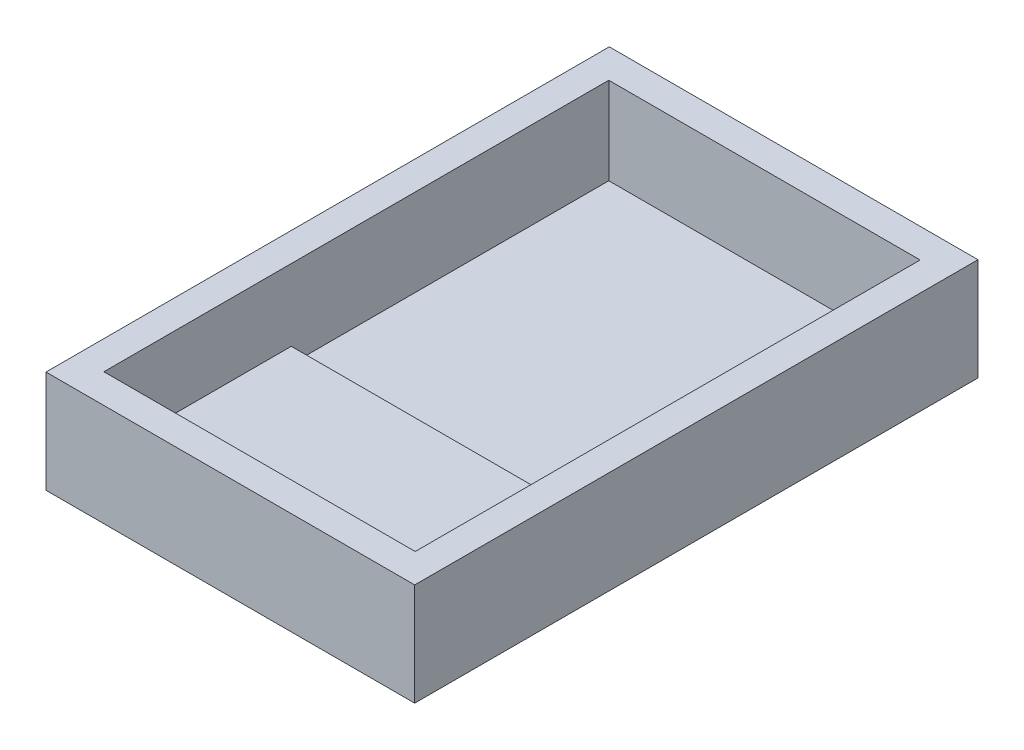
SolidWorks part; units mm, degrees
ref_plane "Front Plane" through (0, 0, 0) normal (0, 0, 1) x (1, 0, 0)
ref_plane "Top Plane" through (0, 0, 0) normal (0, 1, 0) x (1, 0, 0)
ref_plane "Right Plane" through (0, 0, 0) normal (1, 0, 0) x (0, 0, -1)
sketch "Sketch1" plane through (0, 0, 0) normal (0, 1, 0) x (1, 0, 0)
  line L1 (0, 0) -> (36, 0)
  line L2 (0, 0) -> (0, 55)
  line L3 (0, 55) -> (36, 55)
  line L4 (36, 0) -> (36, 55)
  dimension "D1" = 36
  dimension "D2" = 55
extrude "Boss-Extrude1" add sketch "Sketch1" along normal blind 3
sketch "Sketch2" plane through (0, 3, 0) normal (0, 1, 0) x (1, 0, 0)
  line L1 (2.8, 52.15) -> (33.2, 52.15)
  line L2 (2.8, 52.15) -> (2.8, 2.85)
  line L3 (2.8, 2.85) -> (33.2, 2.85)
  line L4 (33.2, 52.15) -> (33.2, 2.85)
  line L8 (0, 55) -> (0, 0)
  line L9 (0, 0) -> (36, 0)
  line L10 (36, 0) -> (36, 55)
  line L11 (36, 55) -> (0, 55)
  line L12 (0, 55) -> (0, 0)
  line L13 (0, 0) -> (36, 0)
  line L14 (36, 0) -> (36, 55)
  line L15 (36, 55) -> (0, 55)
  point P6 (18, 55)
  point P8 (18, 52.15)
  point P10 (0, 27.5)
  point P11 (2.8, 27.5)
  dimension "D2" = 30.4
  dimension "D3" = 49.3
  dimension "D1" = 0
extrude "Boss-Extrude2" add sketch "Sketch2" along normal blind 7
sketch "Sketch3" plane through (0, 3, 0) normal (0, 1, 0) x (1, 0, 0)
  line L0 (33.2, 2.85) -> (33.2, 52.15) construction
  line L1 (2.8, 52.15) -> (33.2, 52.15)
  line L2 (2.8, 52.15) -> (2.8, 21.15)
  line L3 (2.8, 21.15) -> (33.2, 21.15)
  line L4 (33.2, 52.15) -> (33.2, 21.15)
  dimension "D1" = 31
extrude "Cut-Extrude1" cut sketch "Sketch3" against normal blind 1.5
